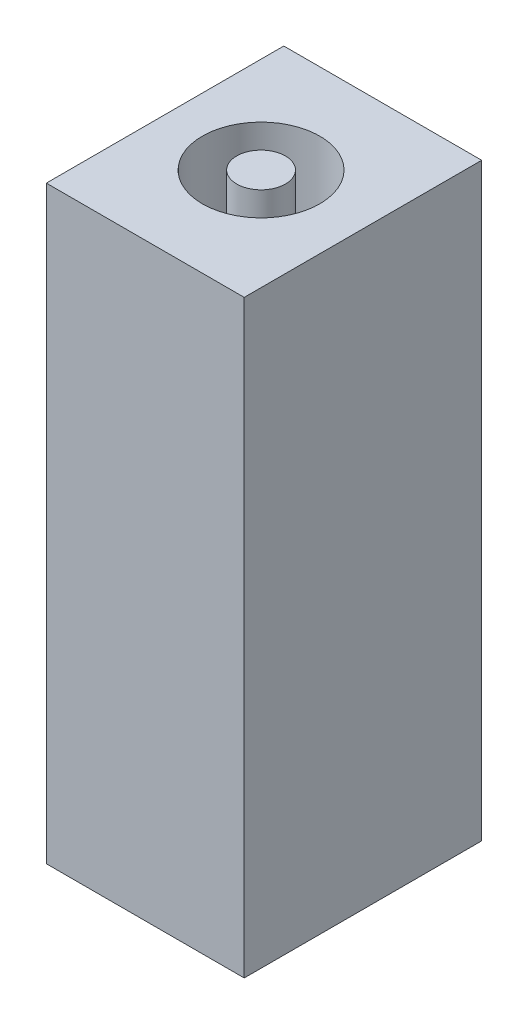
SolidWorks part; units mm, degrees
ref_plane "Front Plane" through (0, 0, 0) normal (0, 0, 1) x (1, 0, 0)
ref_plane "Top Plane" through (0, 0, 0) normal (0, 1, 0) x (1, 0, 0)
ref_plane "Right Plane" through (0, 0, 0) normal (1, 0, 0) x (0, 0, -1)
sketch "Sketch1" plane through (0, 0, 0) normal (1, 0, 0) x (0, 0, -1)
  line L1 (-15, 37.234) -> (15, 37.234)
  line L2 (-15, 37.234) -> (-15, -37.234)
  line L3 (-15, -37.234) -> (15, -37.234)
  line L4 (15, 37.234) -> (15, -37.234)
  line L5 (0, -37.234) -> (0, 37.234) construction
  line L6 (-15, 0) -> (15, 0) construction
  point P0 (0, 0)
extrude "Boss-Extrude1" add sketch "Sketch1" along normal blind 25
sketch "Sketch2" plane through (0, 37.234, 0) normal (0, 1, 0) x (1, 0, 0)
  circle A0 centre (12.1286, 0) radius 7.415
  circle A1 centre (12.1286, 0) radius 3.075
extrude "Cut-Extrude1" cut sketch "Sketch2" against normal blind 64.7
